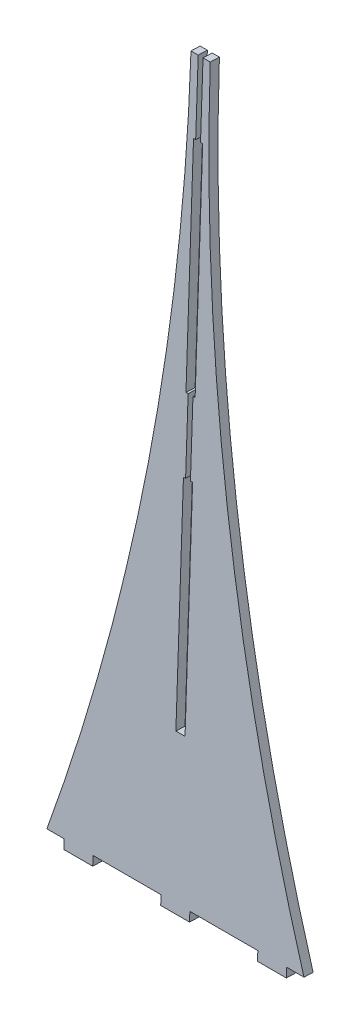
SolidWorks part; units mm, degrees
ref_plane "Front Plane" through (0, 0, 0) normal (0, 0, 1) x (1, 0, 0)
ref_plane "Top Plane" through (0, 0, 0) normal (0, 1, 0) x (1, 0, 0)
ref_plane "Right Plane" through (0, 0, 0) normal (1, 0, 0) x (0, 0, -1)
sketch "Sketch1" plane through (0, -2.4223, -69.3084) normal (0, -0.0349, -0.9994) x (-1, 0, 0)
  line L0 (0, 6.6089) -> (0, -6.6089) construction
  line L1 (3.3375, 329.2146) -> (0.8375, 329.2146)
  line L2 (-44.5715, 79.2146) -> (44.5715, 79.2146)
  line L3 (0.8375, 329.2146) -> (0.8375, 304.2146)
  line L4 (-0.8375, 304.2146) -> (-1.5875, 304.2146)
  line L5 (-3.3375, 329.2146) -> (-0.8375, 329.2146)
  line L6 (-0.8375, 329.2146) -> (-0.8375, 304.2146)
  line L7 (-1.5875, 304.2146) -> (-1.5875, 329.2146) construction
  line L8 (-1.5875, 304.2146) -> (-1.5875, 229.2146)
  line L9 (-1.5875, 229.2146) -> (-0.8375, 229.2146)
  line L10 (-0.8375, 229.2146) -> (-0.8375, 204.2146)
  line L11 (-1.5875, 204.2146) -> (1.5875, 204.2146) construction
  line L12 (-0.8375, 204.2146) -> (-1.5875, 204.2146)
  line L13 (-1.5875, 204.2146) -> (-1.5875, 129.2146)
  line L14 (-1.5875, 129.2146) -> (1.5875, 129.2146)
  line L15 (-1.5875, 129.2146) -> (1.5875, 129.2146) construction
  line L16 (1.5875, 79.2146) -> (1.5875, 129.2146) construction
  line L17 (-1.5875, 229.2146) -> (1.5875, 229.2146) construction
  line L19 (-38.5715, 79.2146) -> (-38.5715, 76.0396)
  line L20 (-38.5715, 76.0396) -> (-28.5715, 76.0396)
  line L21 (-28.5715, 76.0396) -> (-28.5715, 79.2146)
  line L22 (0.8375, 304.2146) -> (1.5875, 304.2146)
  line L23 (1.5875, 304.2146) -> (1.5875, 229.2146)
  line L24 (1.5875, 229.2146) -> (0.8375, 229.2146)
  line L25 (0.8375, 229.2146) -> (0.8375, 204.2146)
  line L26 (0.8375, 204.2146) -> (1.5875, 204.2146)
  line L27 (1.5875, 204.2146) -> (1.5875, 129.2146)
  line L28 (28.5715, 76.0396) -> (28.5715, 79.2146)
  line L29 (38.5715, 76.0396) -> (28.5715, 76.0396)
  line L30 (38.5715, 79.2146) -> (38.5715, 76.0396)
  line L31 (-5, 79.2146) -> (-5, 76.0396)
  line L32 (-5, 76.0396) -> (5, 76.0396)
  line L33 (5, 76.0396) -> (5, 79.2146)
  arc A0 (-44.5715, 79.2146) -> (-3.3375, 329.2146) centre (-781.825, 329.2146) ccw
  arc A1 (44.5715, 79.2146) -> (3.3375, 329.2146) centre (781.825, 329.2146) cw
  point P2 (-44.5715, 79.2146)
  point P53 (0, 76.0396)
  point P56 (0, 79.2146)
  line M3 (1.5875, 79.2146) -> (1.5875, 129.2146)
  line M4 (1.5875, 129.2146) -> (-1.5875, 129.2146)
  line M5 (-1.5875, 129.2146) -> (-1.5875, 79.2146)
  line M6 (-1.5875, 79.2146) -> (1.5875, 79.2146)
  dimension "D1" = 0.75
  dimension "D2" = 2.5
  dimension "D3" = 3.175
  dimension "D4" = 10
  dimension "D5" = 6
extrude "Boss-Extrude1" add sketch "Sketch1" along normal blind 3.175 contours A0 L2 L13 L12 L10 L9 L8 L4 L6 L5 M5 | L2 A1 L1 L3 L22 L23 L24 L25 L26 L27 M3 | L32 L33 L2 L31 M6 | L30 L2 L28 L29 | M6 M3 M4 M5 | L20 L21 L2 L19
